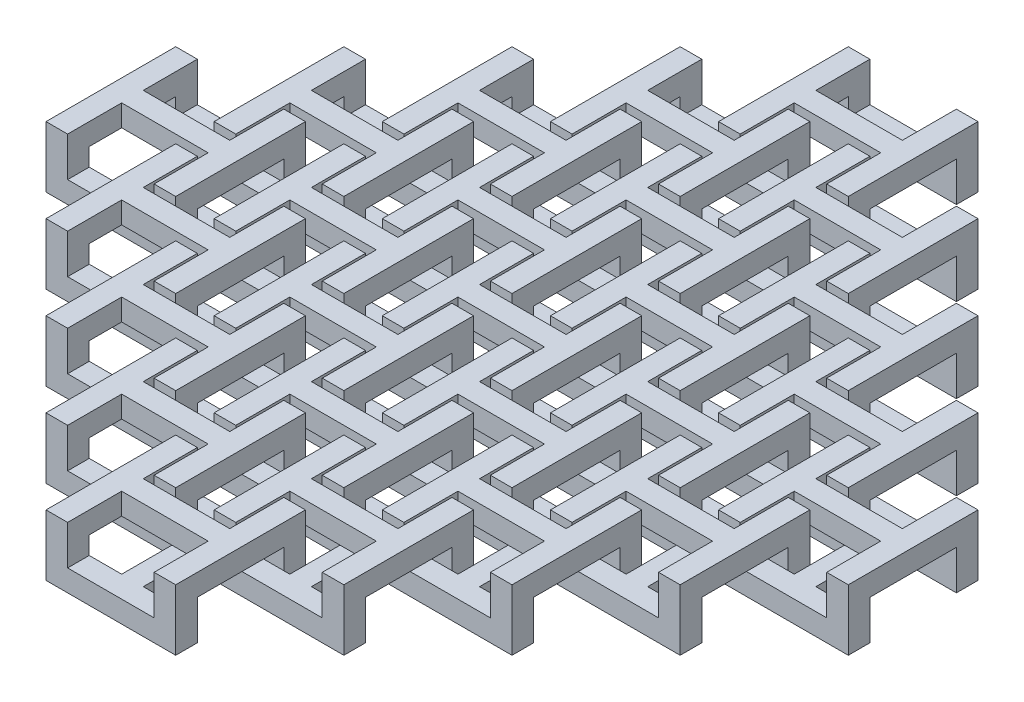
SolidWorks part; units mm, degrees
ref_plane "Front Plane" through (0, 0, 0) normal (0, 0, 1) x (1, 0, 0)
ref_plane "Top Plane" through (0, 0, 0) normal (0, 1, 0) x (1, 0, 0)
ref_plane "Right Plane" through (0, 0, 0) normal (1, 0, 0) x (0, 0, -1)
sketch "Sketch1" plane through (0, 0, 0) normal (0, 1, 0) x (1, 0, 0)
  line L0 (2, 8) -> (7, 8)
  line L1 (-5, 10) -> (7, 10)
  line L2 (-5, 10) -> (-5, 8)
  line L3 (-5, 8) -> (0, 8)
  line L4 (7, 10) -> (7, 8)
  line L6 (0, 8) -> (0, 0)
  line L8 (2, 8) -> (2, 0)
  line L9 (-5, 0) -> (0, 0)
  line L10 (-5, 0) -> (-5, -2)
  line L11 (-5, -2) -> (7, -2)
  line L12 (7, 0) -> (7, -2)
  line L13 (2, 0) -> (7, 0)
  dimension "D1" = 12
  dimension "D2" = 12
  dimension "D3" = 2
  dimension "D4" = 2
  dimension "D5" = 2
extrude "Boss-Extrude1" add sketch "Sketch1" along normal blind 2
sketch "Sketch3" plane through (0, 2, 0) normal (0, 1, 0) x (1, 0, 0)
  line L0 (-5, 8) -> (0, 8) construction
  line L1 (-5, 10) -> (-3, 10)
  line L2 (-5, 10) -> (-5, 8)
  line L3 (-5, 8) -> (-3, 8)
  line L4 (-3, 10) -> (-3, 8)
  line L5 (7, 10) -> (-5, 10) construction
  line L6 (5, 10) -> (7, 10)
  line L7 (5, 10) -> (5, 8)
  line L8 (5, 8) -> (7, 8)
  line L9 (7, 10) -> (7, 8)
  line L10 (7, 0) -> (2, 0) construction
  line L11 (5, 0) -> (7, 0)
  line L12 (5, 0) -> (5, -2)
  line L13 (5, -2) -> (7, -2)
  line L14 (7, 0) -> (7, -2)
  line L15 (0, 0) -> (-5, 0) construction
  line L16 (-3, 0) -> (-5, 0)
  line L17 (-3, 0) -> (-3, -2)
  line L18 (-3, -2) -> (-5, -2)
  line L19 (-5, 0) -> (-5, -2)
  dimension "D1" = 2
extrude "Boss-Extrude3" add sketch "Sketch3" along normal blind 1.65
sketch "Sketch2" plane through (0, 3.65, 0) normal (0, 1, 0) x (1, 0, 0)
  line L0 (-3, -2) -> (5, -2) construction
  line L1 (7, 10) -> (5, 10)
  line L2 (7, 10) -> (7, -2)
  line L3 (7, -2) -> (5, -2)
  line L4 (5, 10) -> (5, 5)
  line L5 (5, 3) -> (5, -2)
  line L6 (5, 5) -> (-3, 5)
  line L8 (5, 3) -> (-3, 3)
  line L10 (-5, 10) -> (-3, 10)
  line L11 (-5, 10) -> (-5, -2)
  line L12 (-5, -2) -> (-3, -2)
  line L13 (-3, 10) -> (-3, 5)
  line L14 (-3, 3) -> (-3, -2)
  dimension "D3" = 2
  dimension "D1" = 2
  dimension "D2" = 2
  dimension "D4" = 12
  dimension "D5" = 12
extrude "Boss-Extrude4" add sketch "Sketch2" along normal blind 2
sketch "Sketch4" plane through (0, 5.65, 0) normal (0, 1, 0) x (1, 0, 0)
  line L0 (-5, 10) -> (35350.3391, -35345.3391) construction
pattern_linear "LPattern1" count 5 spacing 11 along (0.7071, 0, 0.7071) of "Boss-Extrude1", "Boss-Extrude4", "Boss-Extrude3"
sketch "Sketch5" plane through (0, 5.65, 0) normal (0, 1, 0) x (1, 0, 0)
  line L0 (-5, -2) -> (35350.3391, 35353.3391) construction
pattern_linear "LPattern2" count 5 spacing 11 along (0.7071, 0, -0.7071) of bodies 104 105 106 107 108
equation "\"width\"= 12mm"
equation "\"height\"= 4mm"
equation "\"D1@Sketch1\"=\"width\""
equation "\"D2@Sketch1\"=\"width\""
equation "\"lineDepth\"= 2mm"
equation "\"D3@Sketch1\"=\"lineDepth\""
equation "\"D4@Sketch1\"=\"lineDepth\""
equation "\"D5@Sketch1\"=\"lineDepth\""
equation "\"D1@Boss-Extrude1\"=\"lineDepth\""
equation "\"D1@Sketch2\"=\"lineDepth\""
equation "\"D2@Sketch2\"=\"lineDepth\""
equation "\"D3@Sketch2\"=\"lineDepth\""
equation "\"D1@Sketch3\"=\"lineDepth\""
equation "\"D4@Sketch2\"=\"width\""
equation "\"D5@Sketch2\"=\"width\""
equation "\"D1@Boss-Extrude4\"=\"lineDepth\""
